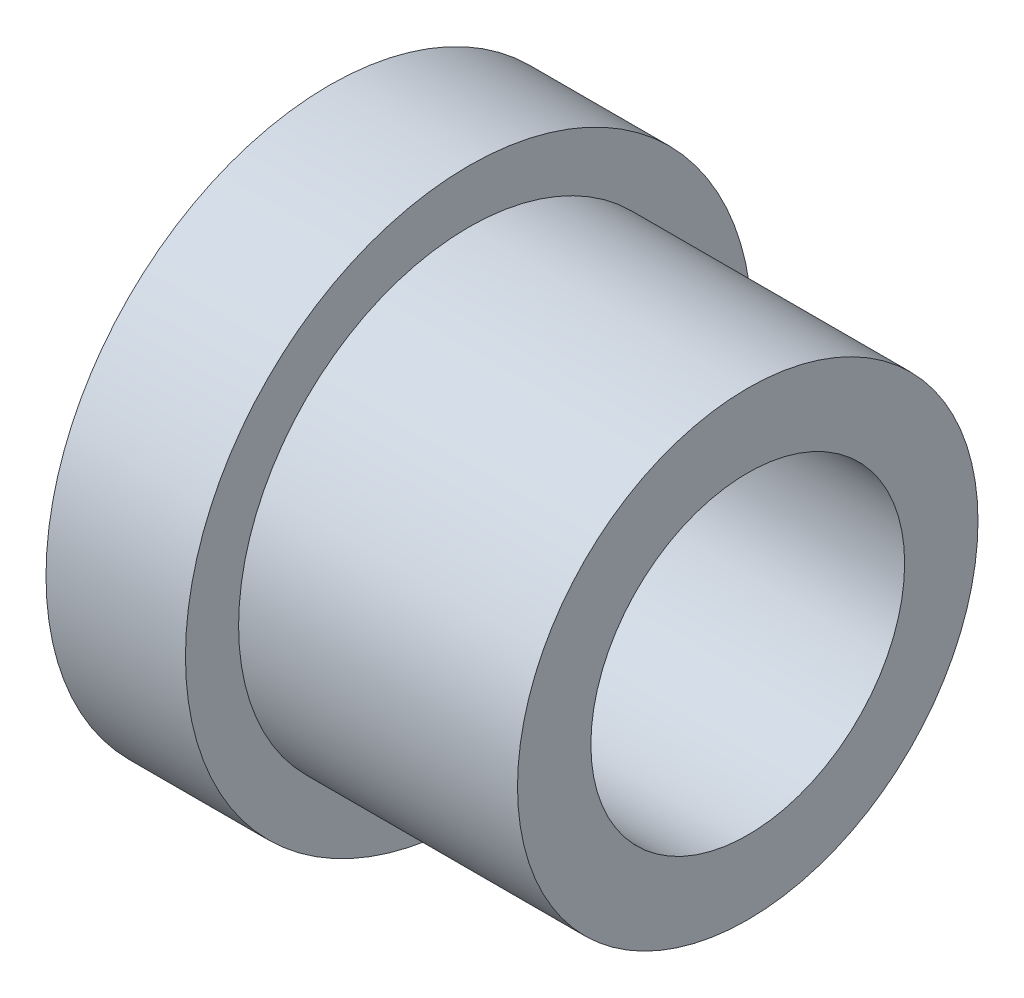
SolidWorks part; units mm, degrees
ref_plane "Front Plane" through (0, 0, 0) normal (0, 0, 1) x (1, 0, 0)
ref_plane "Top Plane" through (0, 0, 0) normal (0, 1, 0) x (1, 0, 0)
ref_plane "Right Plane" through (0, 0, 0) normal (1, 0, 0) x (0, 0, -1)
sketch "Sketch1" plane through (0, 0, 0) normal (0, 1, 0) x (1, 0, 0)
  line L0 (0, 0) -> (36.5528, 0) construction
  line L1 (0, 11.25) -> (0, 20.32)
  line L2 (0, 20.32) -> (10, 20.32)
  line L3 (10, 20.32) -> (10, 16.51)
  line L4 (10, 16.51) -> (30, 16.51)
  line L5 (30, 16.51) -> (30, 11.25)
  line L6 (30, 11.25) -> (12.5, 11.25)
  line L9 (6.5, 8.5) -> (6.5, 11.25)
  line L10 (6.5, 11.25) -> (0, 11.25)
  line L11 (9.5, 8.5) -> (9.5, 4.5)
  line L12 (9.5, 4.5) -> (12.5, 4.5)
  line L14 (12.5, 11.25) -> (12.5, 4.5)
  line L15 (9.5, 8.5) -> (6.5, 8.5)
  point P5 (20, 16.51)
  dimension "D1" = 20.32
  dimension "D2" = 16.51
  dimension "D3" = 11.25
  dimension "D4" = 4.5
  dimension "D5" = 6.5
  dimension "D6" = 8.5
  dimension "D7" = 10
  dimension "D8" = 20
  dimension "D9" = 3
  dimension "D10" = 3
revolve "Revolve1" add sketch "Sketch1" angle 360 about L0
